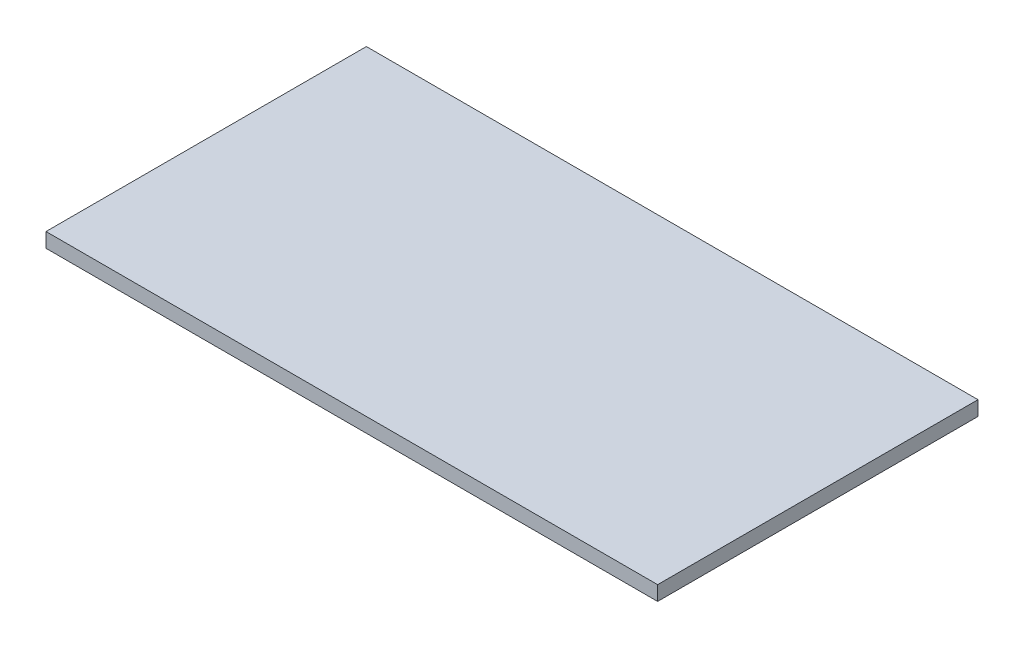
SolidWorks part; units mm, degrees
ref_plane "前视基准面" through (0, 0, 0) normal (0, 0, 1) x (1, 0, 0)
ref_plane "上视基准面" through (0, 0, 0) normal (0, 1, 0) x (1, 0, 0)
ref_plane "右视基准面" through (0, 0, 0) normal (1, 0, 0) x (0, 0, -1)
sketch "草图1" plane through (0, 0, 0) normal (0, 1, 0) x (1, 0, 0)
  line L1 (0, 279.4) -> (533.4, 279.4)
  line L2 (0, 279.4) -> (0, 0)
  line L3 (0, 0) -> (533.4, 0)
  line L4 (533.4, 279.4) -> (533.4, 0)
  dimension "D1" = 279.4
  dimension "D2" = 533.4
extrude "凸台-拉伸1" add sketch "草图1" along normal blind 12.7
sketch "Sketch1" plane through (0, 12.7, 0) normal (0, 1, 0) x (1, 0, 0)
  line L0 (266.7, 25.4) -> (266.7, 0) construction
  line L1 (279.4, 114.3) -> (254, 114.3)
  line L2 (279.4, 114.3) -> (279.4, 25.4)
  line L3 (279.4, 25.4) -> (254, 25.4)
  line L4 (254, 114.3) -> (254, 25.4)
  line L5 (0, 0) -> (533.4, 0) construction
  dimension "D1" = 88.9
  dimension "D2" = 25.4
  dimension "D3" = 25.4
extrude "Cut-Extrude2" [suppressed] cut sketch "Sketch1" against normal up to surface (15.24 mm away) contours L4 L3 L2 L1
sketch "Sketch2" plane through (0, 0, 0) normal (-1, 0, 0) x (0, 0, 1)
  line L0 (-165.1, 12.7) -> (-165.1, 33.02)
  line L1 (-279.4, 12.7) -> (0, 12.7) construction
  line L2 (-165.1, 33.02) -> (-279.4, 12.7)
  line L3 (-165.1, 12.7) -> (-279.4, 12.7)
  dimension "D1" = 114.3
  dimension "D2" = 20.32
extrude "Extrude1" [suppressed] add sketch "Sketch2" against normal blind 254 contours L2 L3 L0
